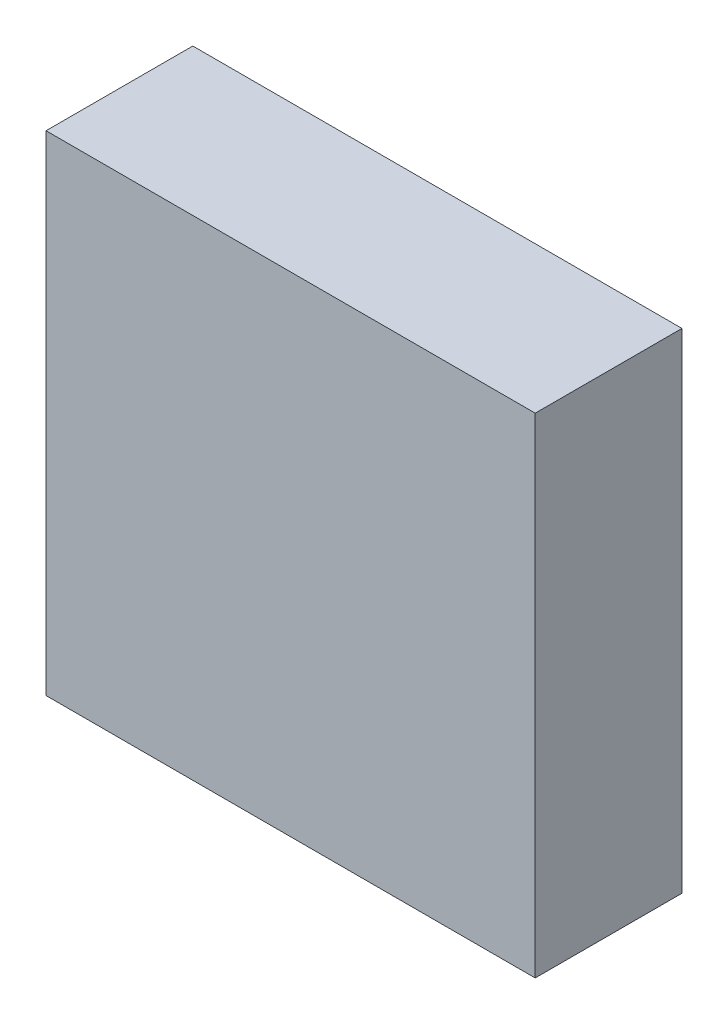
SolidWorks part; units mm, degrees
ref_plane "Front Plane" through (0, 0, 0) normal (0, 0, 1) x (1, 0, 0)
ref_plane "Top Plane" through (0, 0, 0) normal (0, 1, 0) x (1, 0, 0)
ref_plane "Right Plane" through (0, 0, 0) normal (1, 0, 0) x (0, 0, -1)
sketch "Sketch1" plane through (0, 0, 0) normal (0, 0, 1) x (1, 0, 0)
  line L1 (-5, -5) -> (5, -5)
  line L2 (-5, -5) -> (-5, 5)
  line L3 (-5, 5) -> (5, 5)
  line L4 (5, -5) -> (5, 5)
  line L5 (-5, -5) -> (5, 5) construction
  line L6 (-5, 5) -> (5, -5) construction
  point P0 (0, 0)
  dimension "D1" = 10
  dimension "D2" = 10
extrude "Boss-Extrude1" add sketch "Sketch1" along normal blind 3
